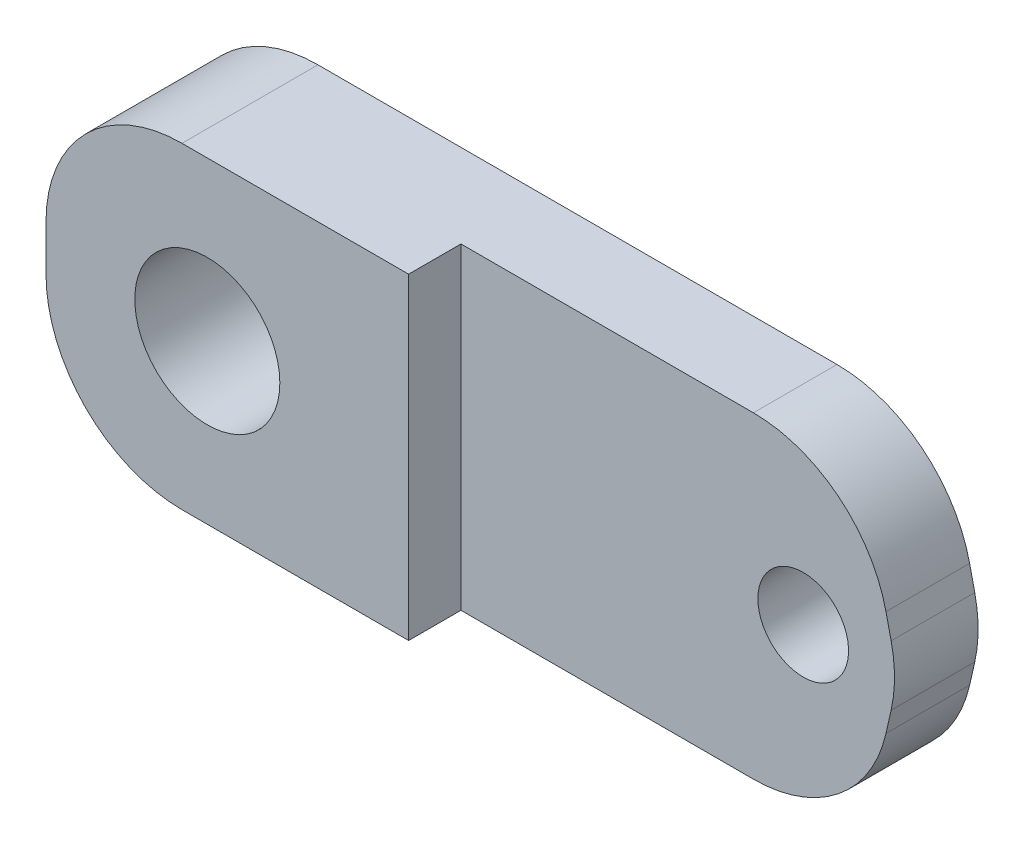
SolidWorks part; units mm, degrees
ref_plane "Ön Düzlem" through (0, 0, 0) normal (0, 0, 1) x (1, 0, 0)
ref_plane "Üst Düzlem" through (0, 0, 0) normal (0, 1, 0) x (1, 0, 0)
ref_plane "Sağ Düzlem" through (0, 0, 0) normal (1, 0, 0) x (0, 0, -1)
sketch "Çizim1" plane through (0, 0, 0) normal (0, 0, 1) x (1, 0, 0)
  line L0 (-19.5, 0.5) -> (-19.5, -0.5)
  line L1 (-16.5, 3.5) -> (-5.0484, 3.5)
  line L3 (-16.5, -3.5) -> (-5.0484, -3.5)
  line L8 (-2.1226, 1.1627) -> (-2.0093, 0.6627)
  line L9 (-2.0093, -0.6627) -> (-2.1226, -1.1627)
  circle A0 centre (-15.9409, 0) radius 1.6
  arc A8 (-16.5, -3.5) -> (-19.5, -0.5) centre (-16.5, -0.5) cw
  arc A9 (-16.5, 3.5) -> (-19.5, 0.5) centre (-16.5, 0.5) ccw
  circle A10 centre (-3.9487, 0) radius 1
  arc A11 (-2.1226, -1.1627) -> (-5.0484, -3.5) centre (-5.0484, -0.5) cw
  arc A12 (-2.0093, 0.6627) -> (-2.0093, -0.6627) centre (-4.9352, 0) cw
  arc A13 (-2.1226, 1.1627) -> (-5.0484, 3.5) centre (-5.0484, 0.5) ccw
  dimension "D1" = 3.2
  dimension "D2" = 3
  dimension "D4" = 2
extrude "Yükseklik-Ekstrüzyon1" add sketch "Çizim1" along normal blind 3
sketch "Çizim2" plane through (0, 0, 0) normal (1, 0, 0) x (0, 0, -1)
  line L0 (-3, -3.5) -> (0, -3.5) construction
  line L1 (-3, 3.5) -> (-1.8454, 3.5)
  line L2 (-3, 3.5) -> (-3, -3.5)
  line L3 (-3, -3.5) -> (-1.8454, -3.5)
  line L4 (-1.8454, 3.5) -> (-1.8454, -3.5)
extrude "Kes-Ekstrüzyon1" cut sketch "Çizim2" against normal mid plane 23
